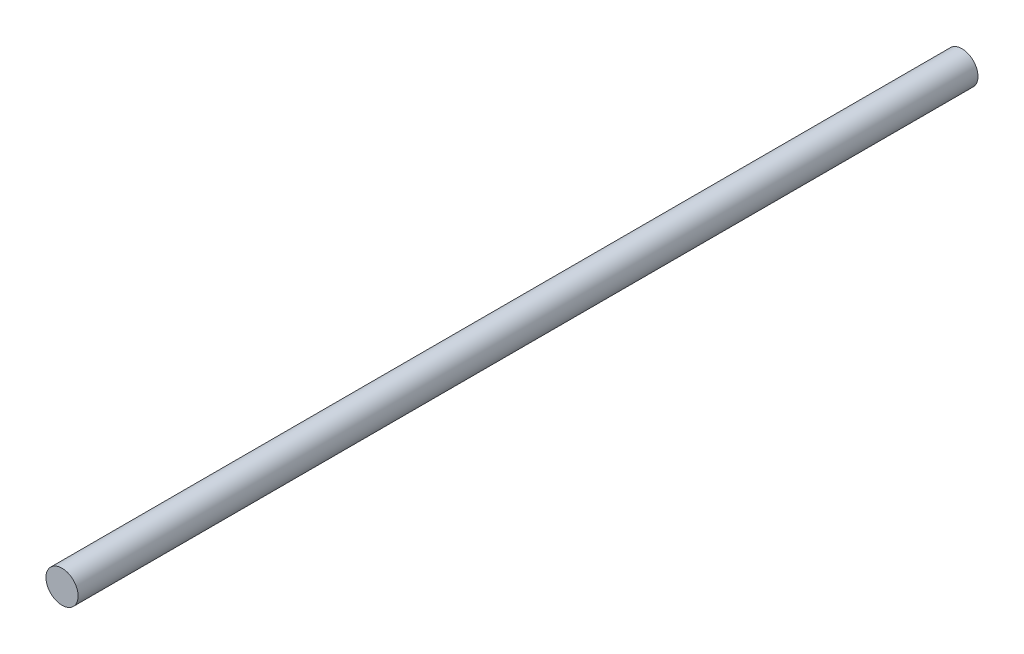
SolidWorks part; units mm, degrees
ref_plane "Front Plane" through (0, 0, 0) normal (0, 0, 1) x (1, 0, 0)
ref_plane "Top Plane" through (0, 0, 0) normal (0, 1, 0) x (1, 0, 0)
ref_plane "Right Plane" through (0, 0, 0) normal (1, 0, 0) x (0, 0, -1)
sketch "Sketch1" plane through (0, 0, 0) normal (0, 0, 1) x (1, 0, 0)
  circle A0 centre (0, 0) radius 6.35
extrude "Boss-Extrude1" add sketch "Sketch1" along normal mid plane 355.6
